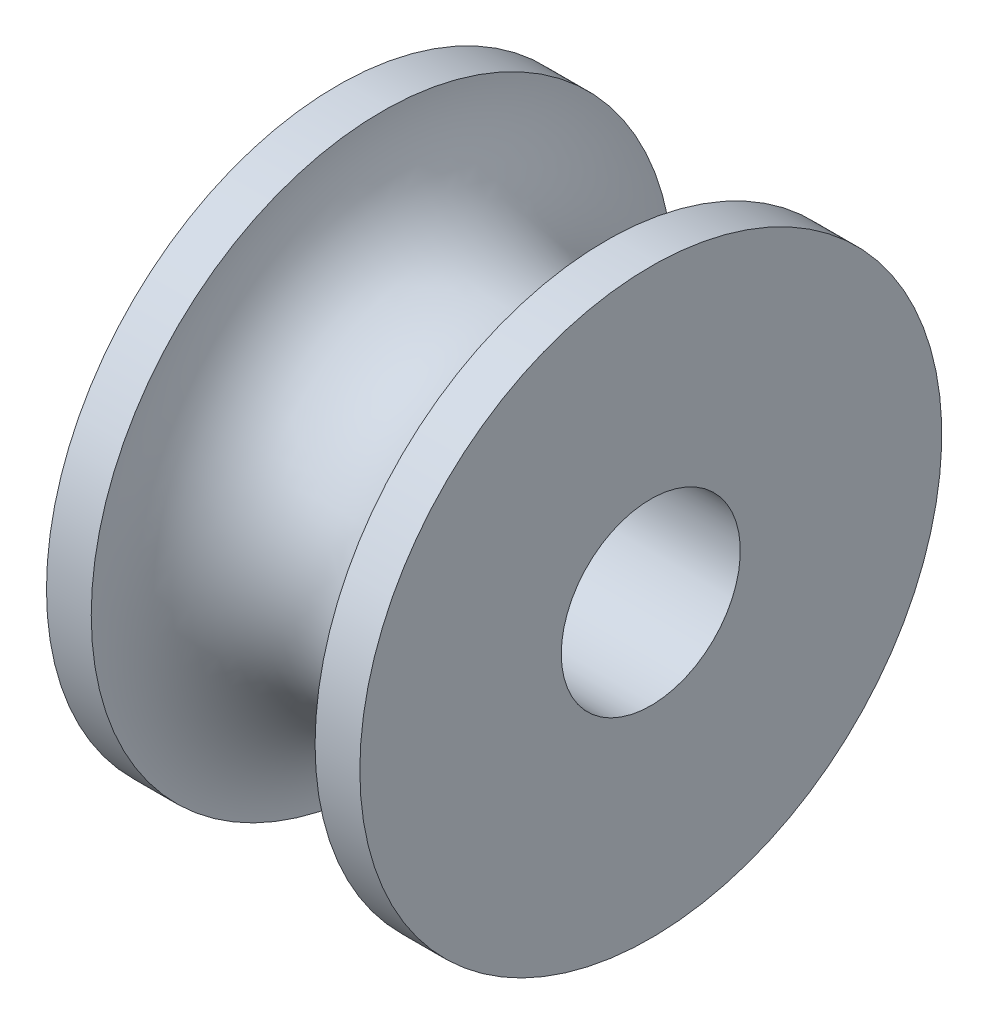
SolidWorks part; units mm, degrees
ref_plane "Front Plane" through (0, 0, 0) normal (0, 0, 1) x (1, 0, 0)
ref_plane "Top Plane" through (0, 0, 0) normal (0, 1, 0) x (1, 0, 0)
ref_plane "Right Plane" through (0, 0, 0) normal (1, 0, 0) x (0, 0, -1)
sketch "Sketch1" plane through (0, 0, 0) normal (0, 0, 1) x (1, 0, 0)
  line L0 (-3.5, 2) -> (-3.5, 6.5)
  line L1 (-3.5, 6.5) -> (-2.5, 6.5)
  line L2 (0, 4) -> (0, 2) construction
  line L3 (3.5, 2) -> (3.5, 6.5)
  line L4 (3.5, 6.5) -> (2.5, 6.5)
  line L5 (-3.5, 2) -> (3.5, 2)
  line L6 (0, 0) -> (8.2872, 0) construction
  arc A0 (-2.5, 6.5) -> (2.5, 6.5) centre (0, 6.5) ccw
  point P5 (0, 0)
  point P11 (0, 0)
  point P12 (8.2872, -1.2599)
  point P15 (0, 0)
  point P16 (0.5998, 2)
  dimension "D1" = 7
  dimension "D2" = 6.5
  dimension "D3" = 2
  dimension "D4" = 1
  dimension "D5" = 4
revolve "Revolve1" add sketch "Sketch1" angle 360 about L6
sketch "Sketch2" plane through (0, 0, 0) normal (1, 0, 0) x (0, 0, -1)
  circle A0 centre (0, 0) radius 4
  circle A1 centre (0, 0) radius 4 construction
  circle A2 centre (0, 0) radius 4.5
  dimension "D1" = 0.5
